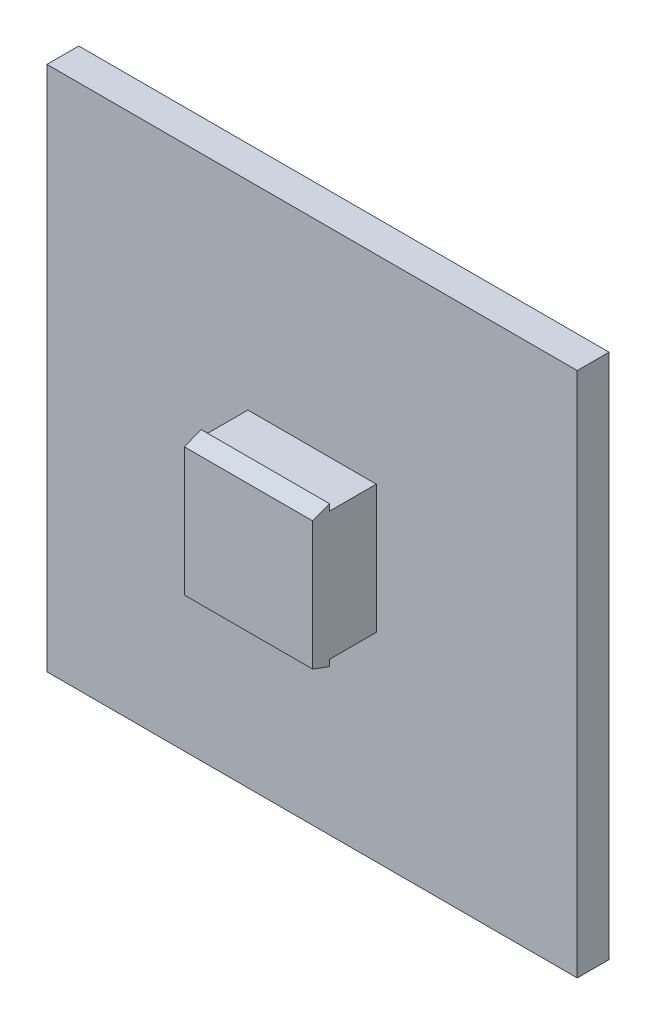
SolidWorks part; units mm, degrees
ref_plane "Front Plane" through (0, 0, 0) normal (1, 0, 0) x (0, 1, 0)
ref_plane "Top Plane" through (0, 0, 0) normal (0, 0, 1) x (0, 1, 0)
ref_plane "Right Plane" through (0, 0, 0) normal (0, 1, 0) x (-1, 0, 0)
sketch "Sketch2" plane through (0, 0, 0) normal (0, 0, 1) x (0, 1, 0)
  line L1 (-12.4, -12.5) -> (12.4, -12.5)
  line L2 (-12.4, -12.5) -> (-12.4, 12.5)
  line L3 (-12.4, 12.5) -> (12.4, 12.5)
  line L4 (12.4, -12.5) -> (12.4, 12.5)
  line L5 (-12.4, -12.5) -> (12.4, 12.5) construction
  line L6 (-12.4, 12.5) -> (12.4, -12.5) construction
  point P0 (0, 0)
  dimension "D1" = 24.8
  dimension "D2" = 25
extrude "Boss-Extrude1" add sketch "Sketch2" along normal blind 1.5
sketch "Sketch3" plane through (0, 0, 1.5) normal (0, 0, 1) x (1, 0, 0)
  line L1 (-3.025, -3.025) -> (3.025, -3.025)
  line L2 (-3.025, -3.025) -> (-3.025, 3.025)
  line L3 (-3.025, 3.025) -> (3.025, 3.025)
  line L4 (3.025, -3.025) -> (3.025, 3.025)
  line L5 (-3.025, -3.025) -> (3.025, 3.025) construction
  line L6 (-3.025, 3.025) -> (3.025, -3.025) construction
  point P0 (0, 0)
  dimension "D1" = 6.05
extrude "Boss-Extrude2" add sketch "Sketch3" along normal blind 3 contours L3 L4 L1 L2
sketch "Sketch4" plane through (-3.025, 0, 0) normal (-1, 0, 0) x (0, -1, 0)
  line L0 (-3.025, 4.5) -> (-3.025, 3.7)
  line L1 (-3.025, 4.5) -> (-3.025, 1.5) construction
  line L2 (-3.025, 3.7) -> (-3.325, 3.7)
  line L3 (-3.325, 3.7) -> (-3.025, 4.5)
  line L4 (0, 4.7058) -> (0, -0.2577) construction
  line L5 (3.325, 3.7) -> (3.025, 4.5)
  line L6 (3.025, 3.7) -> (3.325, 3.7)
  line L7 (3.025, 4.5) -> (3.025, 3.7)
  dimension "D1" = 0.3
  dimension "D2" = 0.8
extrude "Boss-Extrude3" add sketch "Sketch4" against normal up to surface (6.05 mm away) up to face at (3.025, 0, 3)
equation "\"Square_Button_Width\"= 24.8mm"
equation "\"Square_Button_Length\"= 25mm"
equation "\"D1@Sketch2\"=\"Square_Button_Width\""
equation "\"D2@Sketch2\"=\"Square_Button_Length\""
equation "\"Square_Button_Stem_w\"= 6.2mm"
equation "\"Square_Button_Stem_marge\"= 0.15mm"
equation "\"D1@Sketch3\"=\"Square_Button_Stem_w\"-\"Square_Button_Stem_marge\""
equation "\"Square_Button_Stem_Length\"= 3mm"
equation "\"D1@Boss-Extrude2\"=\"Square_Button_Stem_Length\""
